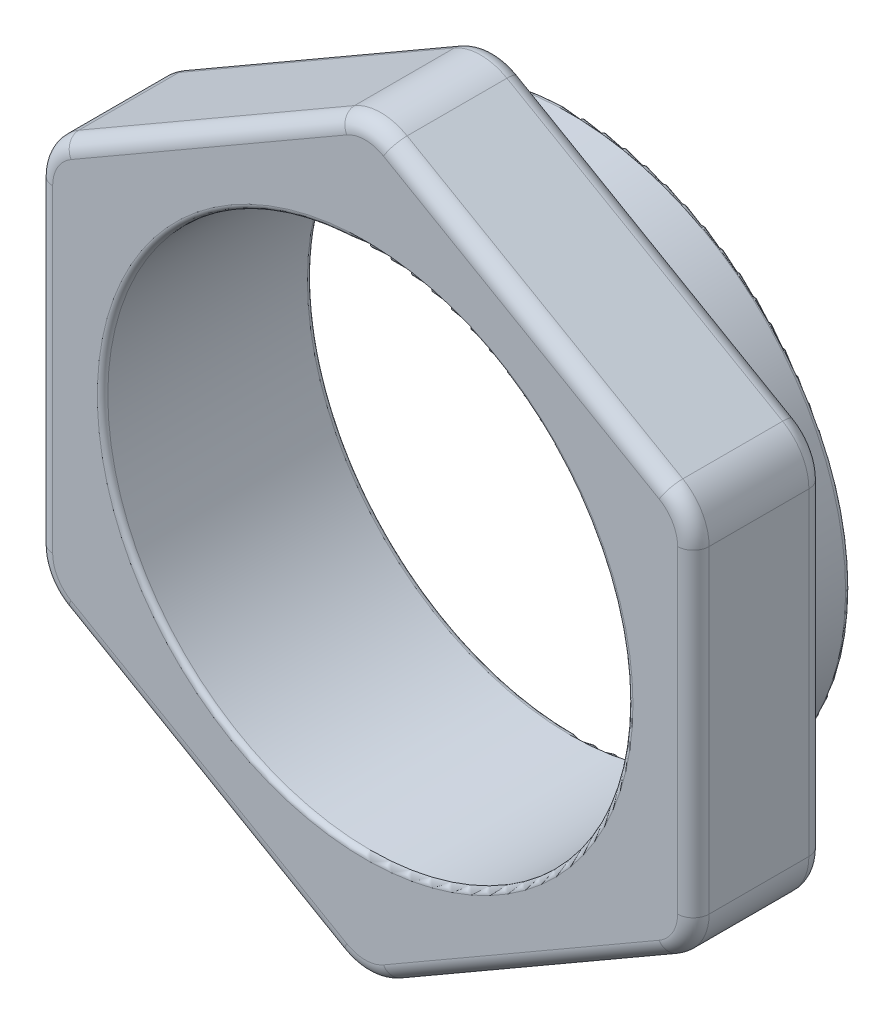
SolidWorks part; units mm, degrees
ref_plane "Front Plane" through (0, 0, 0) normal (0, 0, 1) x (1, 0, 0)
ref_plane "Top Plane" through (0, 0, 0) normal (0, 1, 0) x (1, 0, 0)
ref_plane "Right Plane" through (0, 0, 0) normal (1, 0, 0) x (0, 0, -1)
sketch "Sketch1" plane through (0, 0, 0) normal (0, 0, 1) x (1, 0, 0)
  circle A0 centre (0, 0) radius 6.6675
  dimension "D1" = 13.335
extrude "Boss-Extrude1" add sketch "Sketch1" along normal blind 1.905
sketch "Sketch2" plane through (0, 0, 1.905) normal (0, 0, 1) x (1, 0, 0)
  line L1 (7.9375, 4.5827) -> (0, 9.1654)
  line L2 (0, 9.1654) -> (-7.9375, 4.5827)
  line L3 (-7.9375, 4.5827) -> (-7.9375, -4.5827)
  line L4 (-7.9375, -4.5827) -> (0, -9.1654)
  line L5 (0, -9.1654) -> (7.9375, -4.5827)
  line L6 (7.9375, -4.5827) -> (7.9375, 4.5827)
  circle A0 centre (0, 0) radius 7.9375 construction
  dimension "D1" = 15.875
extrude "Boss-Extrude2" add sketch "Sketch2" along normal blind 3.175
sketch "Sketch3" plane through (0, 0, 0) normal (0, 0, -1) x (-1, 0, 0)
  circle A0 centre (0, 0) radius 6.35
  dimension "D1" = 12.7
extrude "Cut-Extrude1" cut sketch "Sketch3" against normal through all
fillet "Fillet1" radius 1.27 6 edges at (7.9375, -4.5827, 3.4925) (0, -9.1654, 3.4925) (-7.9375, -4.5827, 3.4925) (-7.9375, 4.5827, 3.4925) (7.9375, 4.5827, 3.4925) (0, 9.1654, 3.4925)
fillet "Fillet2" radius 0.381 24 edges at (7.9375, 0, 1.905) (-3.9688, 6.8741, 1.905) (-7.9375, 0, 1.905) (-3.9687, -6.8741, 1.905) (3.9688, -6.8741, 1.905) (7.9375, 0, 5.08) (-3.9688, 6.8741, 5.08) (-7.9375, 0, 5.08) (-3.9687, -6.8741, 5.08) (3.9688, -6.8741, 5.08) (0, 8.969, 1.905) (7.7674, 4.4845, 1.905) (-7.7674, 4.4845, 1.905) (-7.7674, -4.4845, 1.905) (0, -8.969, 1.905) (7.7674, -4.4845, 1.905) (0, 8.969, 5.08) (7.7674, 4.4845, 5.08) (-7.7674, 4.4845, 5.08) (-7.7674, -4.4845, 5.08) (0, -8.969, 5.08) (7.7674, -4.4845, 5.08) (3.9688, 6.8741, 5.08) (3.9688, 6.8741, 1.905)
fillet "Fillet3" radius 0.127 4 edges at (-6.35, 0, 0) (6.6675, 0, 0) (6.6675, 0, 1.905) (-6.35, 0, 5.08)
